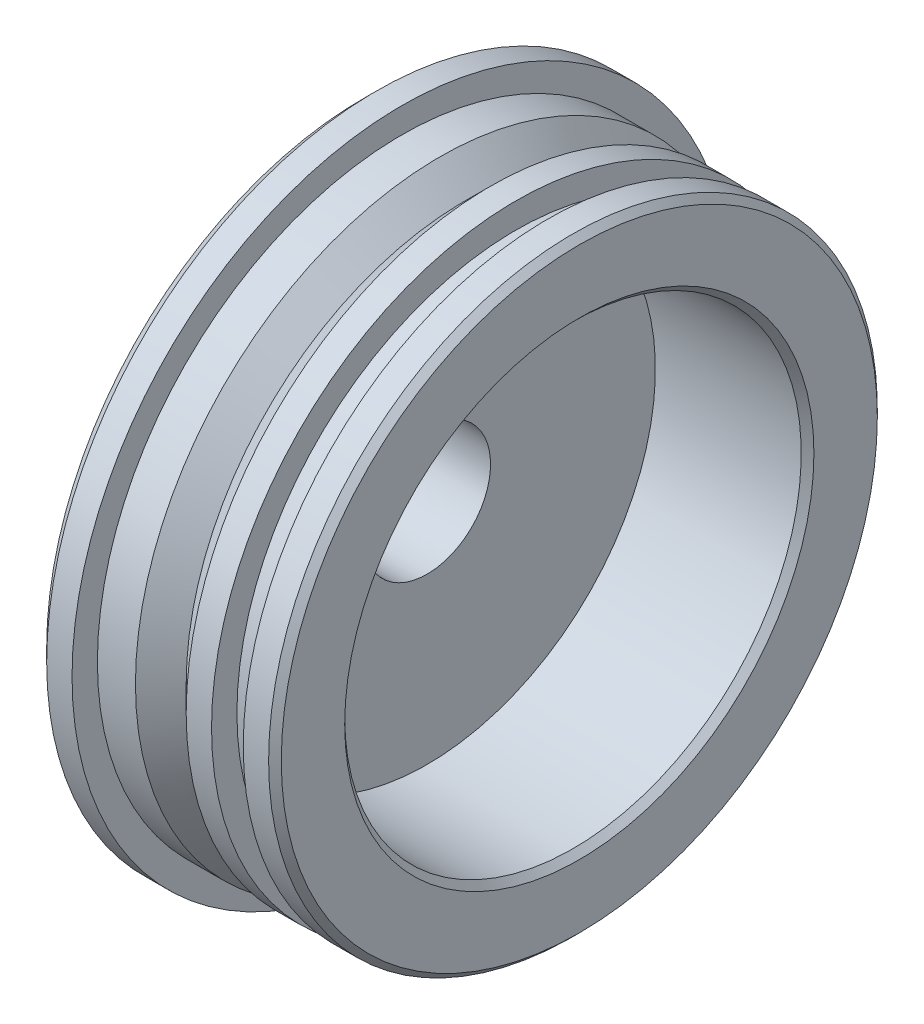
SolidWorks part; units mm, degrees
material "1060 Сплав"
ref_plane "Спереди" through (0, 0, 0) normal (0, 0, 1) x (1, 0, 0)
ref_plane "Сверху" through (0, 0, 0) normal (0, 1, 0) x (1, 0, 0)
ref_plane "Справа" through (0, 0, 0) normal (1, 0, 0) x (0, 0, -1)
sketch "Эскиз1" plane through (0, 0, 0) normal (0, 0, 1) x (1, 0, 0)
  line L0 (0, 0) -> (75.9362, 0) construction
  line L1 (-5, 0) -> (-5, 25)
  line L2 (-4, 26) -> (-2, 26)
  line L3 (-2, 26) -> (-2, 24)
  line L4 (-2, 24) -> (1, 24)
  line L5 (1, 24) -> (3, 22)
  line L6 (3, 22) -> (5, 24)
  line L7 (5, 24) -> (7, 24)
  line L8 (7, 24) -> (7, 22)
  line L9 (7, 22) -> (9.5, 22)
  line L10 (9.5, 22) -> (9.5, 24)
  line L11 (9.5, 24) -> (11.5, 24)
  line L12 (12, 23.5) -> (12, 18.5)
  line L13 (11.5, 18) -> (0, 18)
  line L14 (0, 18) -> (0, 0)
  line L15 (-5, 25) -> (-4, 26)
  line L16 (11.5, 24) -> (12, 23.5)
  line L17 (12, 18.5) -> (11.5, 18)
  line L18 (-5, 0) -> (0, 0)
  point P5 (-5, 26)
  point P16 (12, 24)
  point P17 (12, 18)
  dimension "D1" = 135
  dimension "D2" = 2
  dimension "D3" = 3
  dimension "D4" = 2.5
  dimension "D5" = 6
  dimension "D6" = 2
  dimension "D7" = 5
  dimension "D8" = 2
  dimension "D9" = 2.5
  dimension "D10" = 2
  dimension "D11" = 52
  dimension "D12" = 5
revolve "Повернуть1" add sketch "Эскиз1" angle 360 about L0
sketch "Эскиз2" plane through (-5, 0, 0) normal (-1, 0, 0) x (0, 0, 1)
  circle A0 centre (0, 0) radius 5
  dimension "D1" = 10
extrude "Вырез-Вытянуть1" cut sketch "Эскиз2" against normal blind 10
